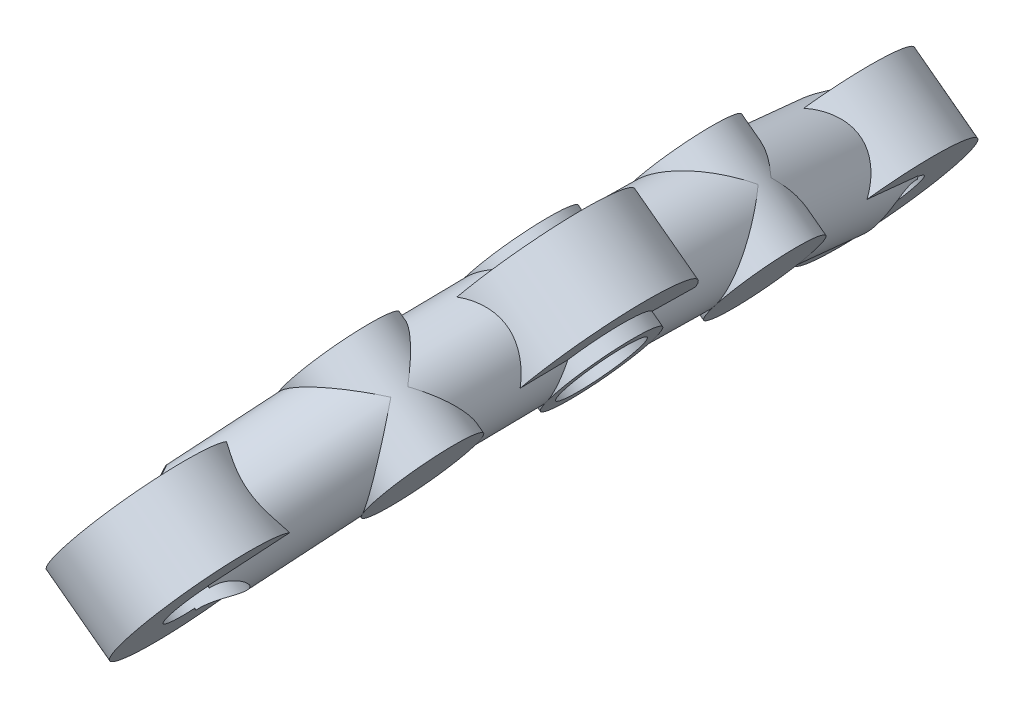
SolidWorks part; units mm, degrees
material "6061-T6 (SS)"
ref_plane "Alzado" through (0, 0, 0) normal (0, 0, 1) x (1, 0, 0)
ref_plane "Planta" through (0, 0, 0) normal (0, 1, 0) x (1, 0, 0)
ref_plane "Vista lateral" through (0, 0, 0) normal (1, 0, 0) x (0, 0, -1)
sketch3d "Sk_Arco_1"
  line L0 (-231.3637, 348.9396, -26) -> (-228.3681, 352.9429, -13)
  dimension "D1" = 13.9284
sweep "Arco_1" add path "Sk_Arco_1" circular profile diameter 8 parameters "D3"=8
sketch3d "Sk_Arco_2"
  line L0 (-228.3681, 352.9429, -13) -> (-227.769, 353.7435, 0)
  dimension "D1" = 13.0384
sweep "Arco_2" add path "Sk_Arco_2" circular profile diameter 8 parameters "D3"=8
sketch3d "Sk_Arco_3"
  line L0 (-227.769, 353.7435, 0) -> (-228.3681, 352.9429, 13)
  dimension "D1" = 13.0384
sweep "Arco_3" add path "Sk_Arco_3" circular profile diameter 8 parameters "D3"=8
sketch3d "Sk_Arco_4"
  line L0 (-228.3681, 352.9429, 13) -> (-231.3637, 348.9396, 26)
  dimension "D1" = 13.9284
sweep "Arco_4" add path "Sk_Arco_4" circular profile diameter 8 parameters "D3"=8
sketch3d "Sk_Arco_codo_1"
  line L0 (-225.1655, 350.5463, -13) -> (-231.5707, 355.3394, -13)
  dimension "D1" = 8
sweep "Arco_codo_1" add path "Sk_Arco_codo_1" circular profile diameter 8 parameters "D3"=8
sketch3d "Sk_Arco_codo_2"
  line L0 (-224.5664, 351.347, 0) -> (-230.9716, 356.14, 0)
  dimension "D1" = 8
sweep "Arco_codo_2" add path "Sk_Arco_codo_2" circular profile diameter 8 parameters "D3"=8
sketch3d "Sk_Arco_codo_3"
  line L0 (-225.1655, 350.5463, 13) -> (-231.5707, 355.3394, 13)
  dimension "D1" = 8
sweep "Arco_codo_3" add path "Sk_Arco_codo_3" circular profile diameter 8 parameters "D3"=8
sketch3d "Sk_Boss_izq"
  line L0 (-228.9618, 347.1422, -26) -> (-233.7657, 350.737, -26)
  dimension "D1" = 6
sweep "Boss_izq" add path "Sk_Boss_izq" circular profile diameter 12 parameters "D3"=12
sketch3d "Sk_Boss_dcho"
  line L0 (-228.9618, 347.1422, 26) -> (-233.7657, 350.737, 26)
  dimension "D1" = 6
sweep "Boss_dcho" add path "Sk_Boss_dcho" circular profile diameter 12 parameters "D3"=12
sketch3d "Sk_Boss_centro"
  line L0 (-225.367, 351.9461, 0) -> (-230.1709, 355.5409, 0)
  dimension "D1" = 6
sweep "Boss_centro" add path "Sk_Boss_centro" circular profile diameter 14 parameters "D3"=14
sketch3d "Sk_Pivote_izq"
  line L0 (-228.1611, 346.5431, -26) -> (-234.5664, 351.3361, -26)
  dimension "D1" = 8
sweep "Pivote_izq" cut path "Sk_Pivote_izq" circular profile diameter 5 parameters "D3"=5
sketch3d "Sk_Pivote_dcho"
  line L0 (-228.1611, 346.5431, 26) -> (-234.5664, 351.3361, 26)
  dimension "D1" = 8
sweep "Pivote_dcho" cut path "Sk_Pivote_dcho" circular profile diameter 5 parameters "D3"=5
sketch3d "Sk_Taladro_tornillo"
  line L0 (-224.5664, 351.347, 0) -> (-230.9716, 356.14, 0)
  dimension "D1" = 8
sweep "Taladro_tornillo" cut path "Sk_Taladro_tornillo" circular profile diameter 6 parameters "D3"=6
